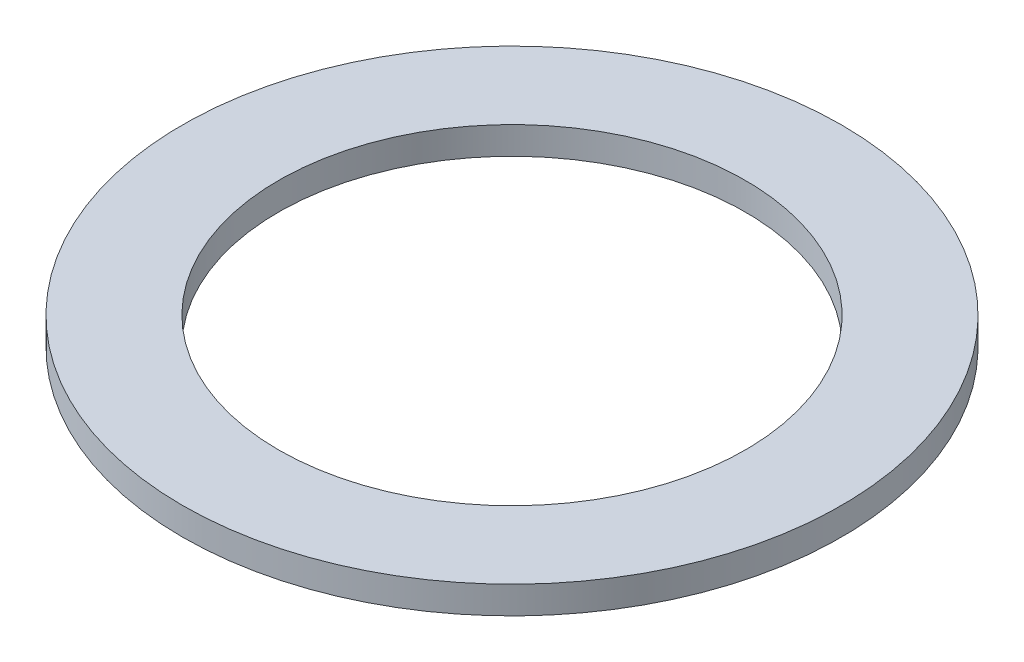
SolidWorks part; units mm, degrees
ref_plane "Front Plane" through (0, 0, 0) normal (0, 0, 1) x (1, 0, 0)
ref_plane "Top Plane" through (0, 0, 0) normal (0, 1, 0) x (1, 0, 0)
ref_plane "Right Plane" through (0, 0, 0) normal (1, 0, 0) x (0, 0, -1)
sketch "Sketch1" plane through (0, 0, 0) normal (0, 1, 0) x (1, 0, 0)
  circle A0 centre (0, 0) radius 76.2
  circle A1 centre (0, 0) radius 53.975
  dimension "D1" = 152.4
  dimension "D2" = 107.95
extrude "Boss-Extrude1" add sketch "Sketch1" along normal mid plane 6.35
equation "\"airframeInnerDiameter\"= 6in"
equation "\"outerDiameter\"= 6.112in"
equation "\"airframeBulkheadThickness\"= 0.125in"
equation "\"payloadAirframeLength\"= 10in"
equation "\"payloadInnerDiameter\"= 6in - 0.056in"
equation "\"payloadOuterDiameter\"= \"airframeInnerDiameter\""
equation "\"payloadLength\"= 11in"
equation "\"payloadBand\"= 2in"
equation "\"payloadOffsetFromAft\"= 6in"
equation "\"upperAirframeLength\"= 25in"
equation "\"recoveryBayInnerDiameter\"= 5.888in"
equation "\"recoveryLength\"= 8in"
equation "\"recoveryBand\"= 2in"
equation "\"recoveryCouplerOuter\"=\"airframeInnerDiameter\""
equation "\"recoveryOffsetFromAft\"= 3in"
equation "\"midAirframeLength\"= 20in"
equation "\"atsLength\"= 11in"
equation "\"atsInner\"= 5.888in"
equation "\"atsBand\"= 2in"
equation "\"atsCouplerOuter\"=\"airframeInnerDiameter\""
equation "\"atsOffsetFromAft\"= 3in"
equation "\"lowerAirframeLength\"= 40in"
equation "\"finSlotLength\"= 8in"
equation "\"finSlotOffsetFromAft\"= 3in"
equation "\"finSlotWidth\"= 0.187in"
equation "\"D1@Sketch1\"=\"centeringRingOuterDiameter\""
equation "\"motorTubeOuterDiameter\"= 4.25in"
equation "\"motorTubeInnerDiameter\"= 4in"
equation "\"motorTubeLength\"= 32in"
equation "\"centeringRingOuterDiameter\"= \"airframeInnerDiameter\""
equation "\"centeringRingInnerDiameter\"= \"motorTubeOuterDiameter\""
equation "\"D2@Sketch1\"=\"centeringRingInnerDiameter\""
equation "\"centeringRingThickness\"= 0.25in"
equation "\"topCenteringRingOffsetFromAft\"= 16.7in"
equation "\"bottomCenteringRingOffsetFromAft\"= 0.3in"
equation "\"D1@Boss-Extrude1\"=\"centeringRingThickness\""
equation "\"atsFlapWidth\" = 1.5in"
equation "\"atsFlapThickness\" = 0.125in"
equation "\"motorCasingOuterDiameter\"= 3in"
equation "\"motorCasingCenteringRingThickness\"= 0.25in"
